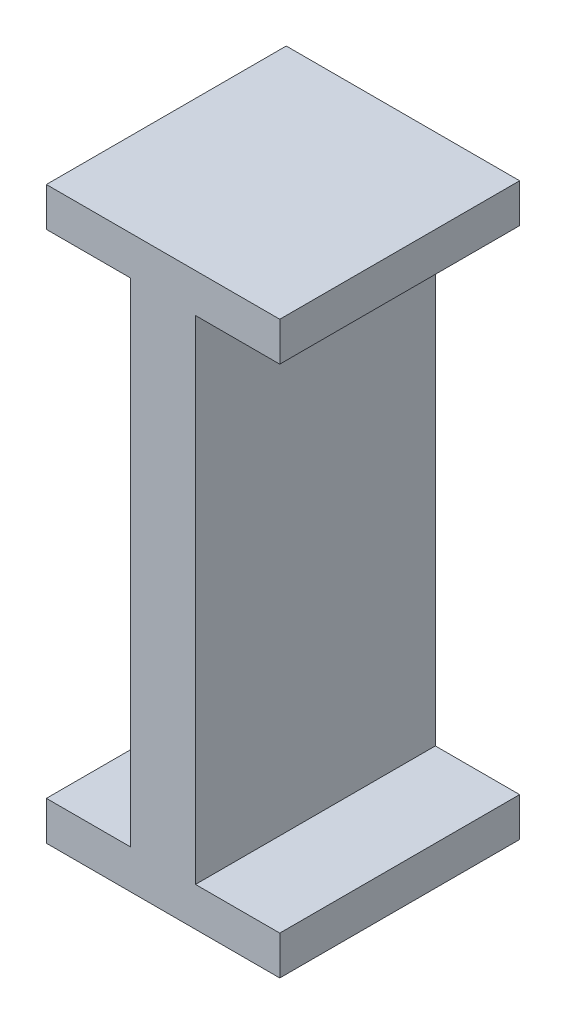
SolidWorks part; units mm, degrees
material "AISI 1010 钢，热轧条材"
ref_plane "前视基准面" through (0, 0, 0) normal (0, 0, 1) x (1, 0, 0)
ref_plane "上视基准面" through (0, 0, 0) normal (0, 1, 0) x (1, 0, 0)
ref_plane "右视基准面" through (0, 0, 0) normal (1, 0, 0) x (0, 0, -1)
sketch "草图1" plane through (0, 0, 0) normal (0, 1, 0) x (1, 0, 0)
  line L1 (-18, -18.5) -> (18, -18.5)
  line L2 (-18, -18.5) -> (-18, 18.5)
  line L3 (-18, 18.5) -> (18, 18.5)
  line L4 (18, -18.5) -> (18, 18.5)
  line L5 (-18, -18.5) -> (18, 18.5) construction
  line L6 (-18, 18.5) -> (18, -18.5) construction
  point P0 (0, 0)
  dimension "D1" = 37
  dimension "D2" = 36
extrude "凸台-拉伸1" add sketch "草图1" along normal blind 6
sketch "草图2" plane through (0, 6, 0) normal (0, 1, 0) x (1, 0, 0)
  line L0 (-18, -18.5) -> (18, -18.5) construction
  line L1 (5, 18.5) -> (-5, 18.5)
  line L2 (5, 18.5) -> (5, -18.5)
  line L3 (5, -18.5) -> (-5, -18.5)
  line L4 (-5, 18.5) -> (-5, -18.5)
  line L5 (5, 18.5) -> (-5, -18.5) construction
  line L6 (5, -18.5) -> (-5, 18.5) construction
  point P0 (0, 0)
  dimension "D1" = 10
extrude "凸台-拉伸2" add sketch "草图2" along normal blind 76
sketch "草图3" plane through (0, 82, 0) normal (0, 1, 0) x (1, 0, 0)
  line L1 (-18, 18.5) -> (18, 18.5)
  line L2 (-18, 18.5) -> (-18, -18.5)
  line L3 (-18, -18.5) -> (18, -18.5)
  line L4 (18, 18.5) -> (18, -18.5)
extrude "凸台-拉伸3" add sketch "草图3" along normal blind 6
